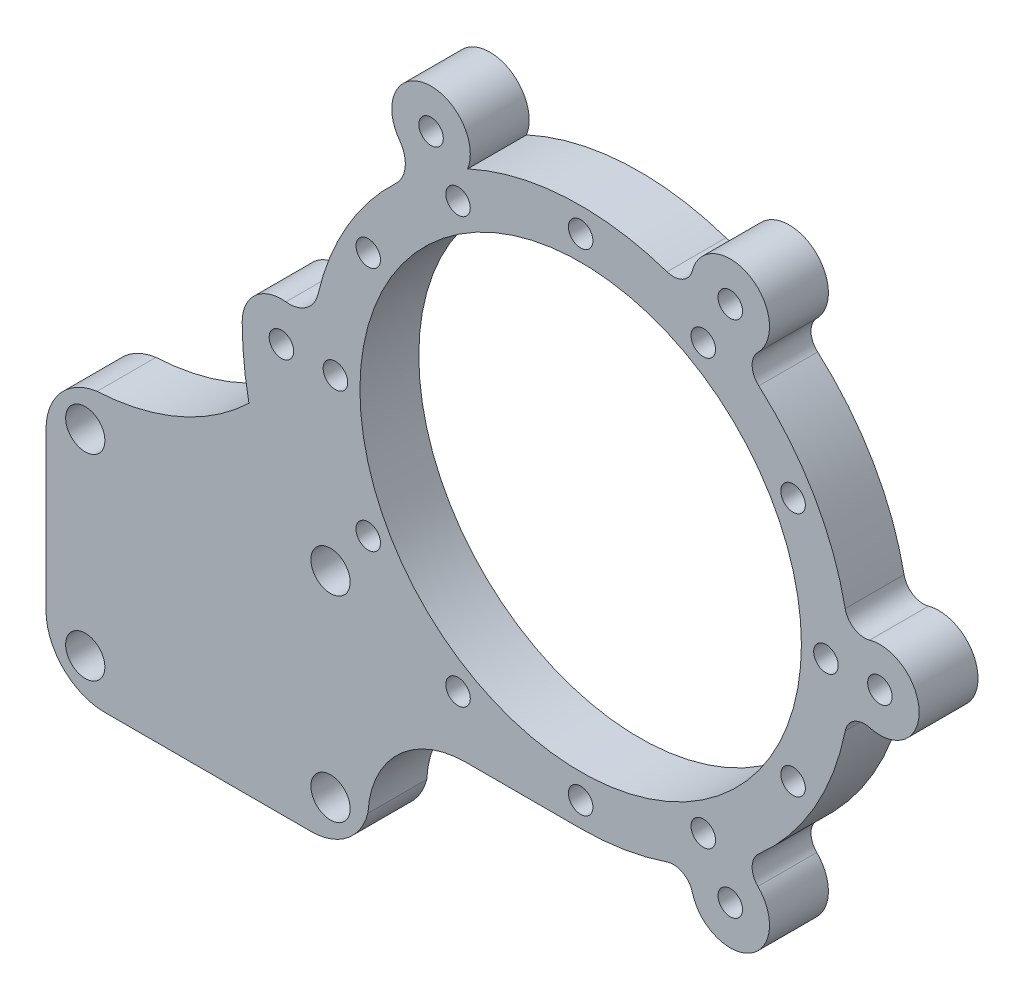
SolidWorks part; units mm, degrees
material "6061 合金"
ref_plane "前视基准面" through (0, 0, 0) normal (0, 0, 1) x (1, 0, 0)
ref_plane "上视基准面" through (0, 0, 0) normal (0, 1, 0) x (1, 0, 0)
ref_plane "右视基准面" through (0, 0, 0) normal (1, 0, 0) x (0, 0, -1)
other "Configuration Table"
sketch "草图2" plane through (0, 0, 0) normal (0, 0, 1) x (1, 0, 0)
  line L0 (0, 0) -> (0, 40) construction
  line L1 (-10.5, 14) -> (10.5, 14)
  line L2 (-16.5, 8) -> (-16.5, -8)
  line L3 (-10.5, -14) -> (10.5, -14)
  line L4 (16.5, 8) -> (16.5, -8)
  line L5 (-16.5, 14) -> (16.5, -14) construction
  line L6 (-16.5, -14) -> (16.5, 14) construction
  line L7 (-12.5, 10) -> (12.5, 10) construction
  line L8 (-12.5, 10) -> (-12.5, -10) construction
  line L9 (-12.5, -10) -> (12.5, -10) construction
  line L10 (12.5, 10) -> (12.5, -10) construction
  line L11 (-12.5, 10) -> (12.5, -10) construction
  line L12 (-12.5, -10) -> (12.5, 10) construction
  line L13 (26.298, 0) -> (77.1914, 0)
  line L14 (-12.5, 37.992) -> (-10.5, 14) construction
  circle A0 centre (12.5, 10) radius 2
  circle A1 centre (12.5, -10) radius 2
  circle A2 centre (-12.5, -10) radius 2
  circle A3 centre (-12.5, 10) radius 2
  arc A4 (10.5, -14) -> (16.5, -8) centre (10.5, -8) ccw
  arc A5 (-10.5, -14) -> (-16.5, -8) centre (-10.5, -8) cw
  arc A6 (-10.5, 14) -> (-16.5, 8) centre (-10.5, 8) ccw
  arc A7 (10.5, 14) -> (16.5, 8) centre (10.5, 8) cw
  arc A8 (-11.2967, 13.9469) -> (11.0718, 33.0943) centre (-12.5, 37.992) ccw
  arc A9 (26.298, 0) -> (16.3107, -9.4952) centre (26.298, -10) ccw
  arc A10 (37.9967, 0) -> (11.0718, 33.0943) centre (37.9967, 27.5) ccw
  circle A11 centre (37.9967, 27.5) radius 22.5
  circle A12 centre (37.9967, 27.5) radius 25 construction
  circle A13 centre (37.9967, 52.5) radius 1.25
  circle A14 centre (50.4967, 49.1506) radius 1.25
  circle A15 centre (59.6473, 40) radius 1.25
  circle A16 centre (62.9967, 27.5) radius 1.25
  circle A17 centre (59.6473, 15) radius 1.25
  circle A18 centre (50.4967, 5.8494) radius 1.25
  circle A19 centre (37.9967, 2.5) radius 1.25
  circle A20 centre (25.4967, 5.8494) radius 1.25
  circle A21 centre (16.3461, 15) radius 1.25
  circle A22 centre (12.9967, 27.5) radius 1.25
  circle A23 centre (16.3461, 40) radius 1.25
  circle A24 centre (25.4967, 49.1506) radius 1.25
  point P0 (0, 0)
  point P6 (0, 0)
  point P54 (37.9967, 27.5)
  dimension "D1" = 4
  dimension "D6" = 6
  dimension "D8" = 55
  dimension "D10" = 20
  dimension "D11" = 45
  dimension "D12" = 12
  dimension "D13" = 2.5
  dimension "D2" = 28
  dimension "D3" = 33
  dimension "D4" = 25
  dimension "D5" = 20
  dimension "D7" = 40
  dimension "D9" = 40
extrude "凸台-拉伸1" add sketch "草图2" along normal blind 6 contours L13 A10 A8 L1 A7 L4 A9 A18 A17 A16 A15 A14 A13 A11 | A9 L4 A7 L1 A8 A6 L2 A5 L3 A4 A3 A2 A1 A0
sketch "草图3" plane through (0, 0, 6) normal (0, 0, 1) x (1, 0, 0)
  line L0 (37.9967, 27.5) -> (37.9967, 62) construction
  circle A0 centre (37.9967, 27.5) radius 34.5
  circle A1 centre (37.9967, 27.5) radius 30.5 construction
  circle A2 centre (37.9967, 27.5) radius 27.5
  circle A3 centre (53.2467, 53.9138) radius 1.25
  circle A4 centre (68.4967, 27.5) radius 1.25
  circle A5 centre (53.2467, 1.0862) radius 1.25
  circle A6 centre (22.7467, 1.0862) radius 1.25
  circle A7 centre (7.4967, 27.5) radius 1.25
  circle A8 centre (22.7467, 53.9138) radius 1.25
  circle A11 centre (37.9967, 27.5) radius 29.5 construction
  circle A13 centre (22.7467, 53.9138) radius 4
  arc A14 (49.3793, 54.9351) -> (46.805, 53.5512) centre (47.4456, 55.4458) cw
  arc A15 (55.2467, 57.3779) -> (49.332, 54.7353) centre (53.2467, 53.9138) ccw
  arc A16 (56.0649, 51.0752) -> (55.2467, 57.3779) centre (53.2467, 53.9138) ccw
  arc A17 (56.0649, 51.0752) -> (56.1536, 48.1538) centre (57.474, 49.6559) ccw
  arc A18 (67.4475, 31.36) -> (64.9618, 32.8974) centre (66.9229, 33.2899) cw
  arc A19 (72.4967, 27.5) -> (67.2508, 31.301) centre (68.4967, 27.5) ccw
  arc A20 (67.4475, 23.64) -> (72.4967, 27.5) centre (68.4967, 27.5) ccw
  arc A21 (67.4475, 23.64) -> (64.9618, 22.1026) centre (66.9229, 21.7101) ccw
  arc A22 (56.0649, 3.9248) -> (56.1536, 6.8462) centre (57.474, 5.3441) cw
  arc A23 (55.2467, -2.3779) -> (55.9155, 4.0657) centre (53.2467, 1.0862) ccw
  arc A24 (49.3793, 0.0649) -> (55.2467, -2.3779) centre (53.2467, 1.0862) ccw
  arc A25 (49.3793, 0.0649) -> (46.805, 1.4488) centre (47.4456, -0.4458) ccw
  circle A26 centre (7.4967, 27.5) radius 4
  arc A28 (26.6141, 54.9351) -> (29.1884, 53.5512) centre (28.5478, 55.4458) ccw
  arc A29 (7.7605, 31.5027) -> (11.221, 33.7698) centre (8.3, 34.4538) ccw
  arc A30 (8.7446, 23.6834) -> (11.0316, 22.1026) centre (9.0705, 21.7101) cw
  arc A32 (19.1791, 47.5536) -> (19.4122, 51.684) centre (17.1262, 49.7412) ccw
  arc A35 (20.7467, 57.3779) -> (20.0779, 50.9343) centre (22.7467, 53.9138) ccw
  arc A38 (26.6141, 0.0649) -> (26.676, 0.2586) centre (28.5478, -0.4458) cw [skipped]
  arc A39 (26.6141, 0.0649) -> (26.6614, 0.2647) centre (22.7467, 1.0862) ccw [skipped]
  arc A41 (3.4967, 27.5) -> (7.759, 23.5086) centre (7.4967, 27.5) ccw [skipped]
  arc A43 (19.9285, 51.0752) -> (19.8399, 48.1538) centre (18.5194, 49.6559) cw [skipped]
  point P21 (37.9967, 27.5)
  point P87 (37.9967, 27.5)
  dimension "D1" = 69
  dimension "D2" = 61
  dimension "D3" = 55
  dimension "D5" = 2.5
  dimension "D6" = 59
  dimension "D7" = 6
  dimension "D8" = 4
  dimension "D4" = 6
extrude "凸台-拉伸2" add sketch "草图3" against normal blind 6
